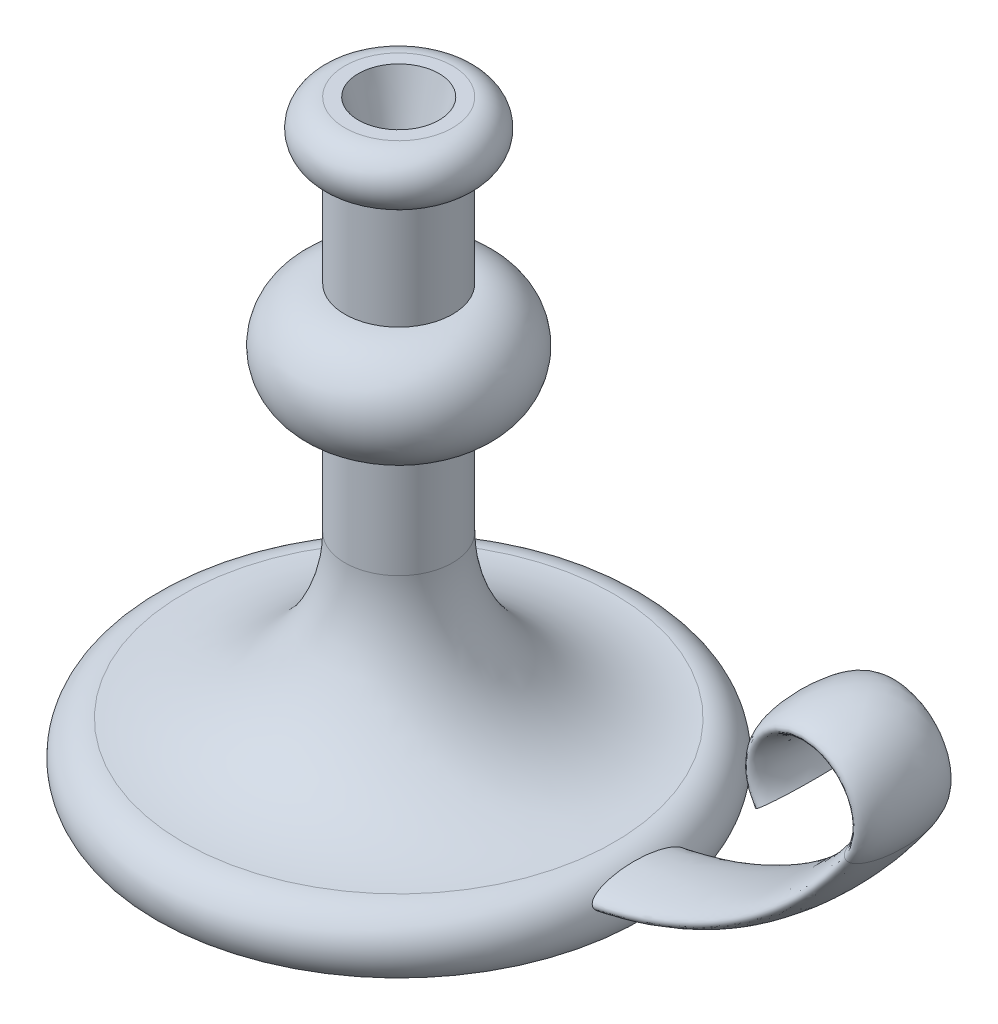
SolidWorks part; units mm, degrees
ref_plane "Front Plane" through (0, 0, 0) normal (0, 0, 1) x (1, 0, 0)
ref_plane "Top Plane" through (0, 0, 0) normal (0, 1, 0) x (1, 0, 0)
ref_plane "Right Plane" through (0, 0, 0) normal (1, 0, 0) x (0, 0, -1)
sketch "Sketch1" plane through (0, 0, 0) normal (0, 0, 1) x (1, 0, 0)
  line L0 (0, 0) -> (0, 220)
  line L1 (0, 220) -> (20, 220)
  line L2 (0, 0) -> (90, 0)
  line L3 (20, 200) -> (20, 160)
  line L4 (20, 120) -> (20, 80)
  arc A0 (20, 220) -> (20, 200) centre (20, 210) cw
  arc A1 (20, 160) -> (20, 120) centre (20, 140) cw
  arc A2 (20, 80) -> (80, 20) centre (80, 80) ccw
  arc A3 (80, 20) -> (90, 0) centre (80, 7.5) cw
  dimension "D5" = 20
  dimension "D7" = 60
  dimension "D8" = 12.5
  dimension "D1" = 220
  dimension "D2" = 20
  dimension "D3" = 90
  dimension "D4" = 10
  dimension "D6" = 40
  dimension "D9" = 80
revolve "Revolve1" add sketch "Sketch1" angle 360 about L0
sketch "Sketch2" plane through (0, 0, 0) normal (0, 0, 1) x (1, 0, 0)
  line L0 (0, 10) -> (60, 10)
  line L1 (0, 227.4356) -> (0, 175.1288) construction
  line L2 (0, 200) -> (0, 160) construction
  line L3 (-90, 0) -> (90, 0) construction
  arc A0 (60, 10) -> (183.5921, 75) centre (60, 160) ccw
  arc A1 (183.5921, 75) -> (150.6342, 75) centre (167.1131, 86.3333) ccw
  dimension "D2" = 150
  dimension "D3" = 65
  dimension "D4" = 20
  dimension "D1" = 60
  dimension "D5" = 10
sketch "Sketch3" plane through (0, 0, 0) normal (1, 0, 0) x (0, 0, -1)
  ellipse E0 centre (0, 10) end of major axis (17.5, 10) minor radius 5
  point P1 (130.0569, 59.3965)
  dimension "D1" = 35
  dimension "D2" = 10
sweep "Sweep1" add profiles "Sketch3" path "Sketch2"
sketch "Sketch4" plane through (0, 220, 0) normal (0, 1, 0) x (1, 0, 0)
  circle A0 centre (0, 0) radius 15
  dimension "D1" = 30
extrude "Cut-Extrude1" cut sketch "Sketch4" against normal blind 25 draft 15
